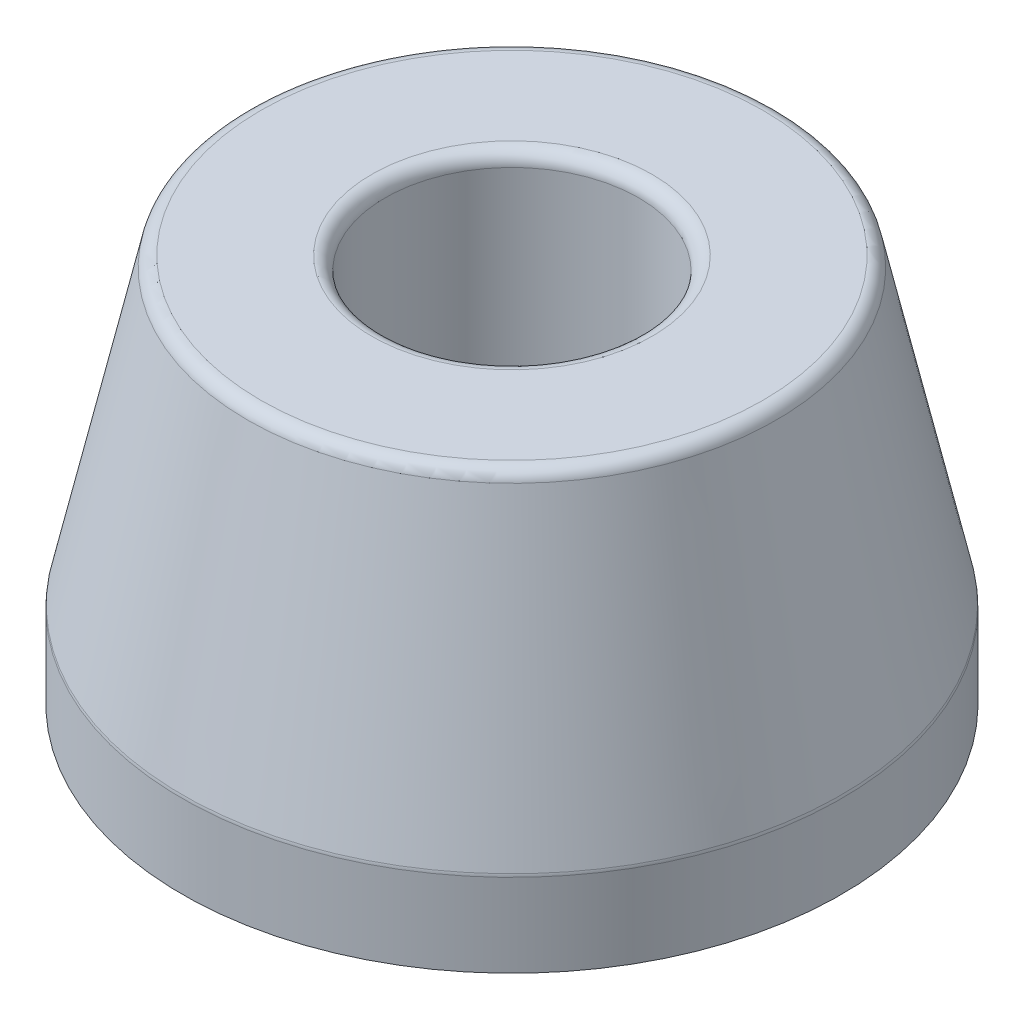
SolidWorks part; units mm, degrees
material "POLYURETHANE (11671)"
ref_plane "Front" through (0, 0, 0) normal (0, 0, 1) x (1, 0, 0)
ref_plane "Top" through (0, 0, 0) normal (0, 1, 0) x (1, 0, 0)
ref_plane "Right" through (0, 0, 0) normal (1, 0, 0) x (0, 0, -1)
sketch "Sketch1" plane through (0, 0, 0) normal (0, 0, 1) x (1, 0, 0)
  line L0 (4.7625, 0) -> (4.7625, 14.097)
  line L1 (5.2705, 14.605) -> (9.435, 14.605)
  line L2 (9.9309, 14.2072) -> (12.3704, 3.2294)
  line L3 (12.3825, 3.1192) -> (12.3825, 0)
  line L4 (12.3825, 0) -> (4.7625, 0)
  line L5 (0, 0) -> (0, 14.605) construction
  arc A0 (12.3704, 3.2294) -> (12.3825, 3.1192) centre (11.8745, 3.1192) cw
  arc A1 (4.7625, 14.097) -> (5.2705, 14.605) centre (5.2705, 14.097) cw
  arc A2 (9.435, 14.605) -> (9.9309, 14.2072) centre (9.435, 14.097) cw
  point P8 (12.3825, 3.175)
  point P11 (4.7625, 14.605)
  point P14 (9.8425, 14.605)
  dimension "D6" = 0.508
  dimension "D1" = 14.605
  dimension "D2" = 4.7625
  dimension "D3" = 5.08
  dimension "D4" = 3.175
  dimension "D5" = 7.62
revolve "Revolve1" add sketch "Sketch1" angle 360 about L5
